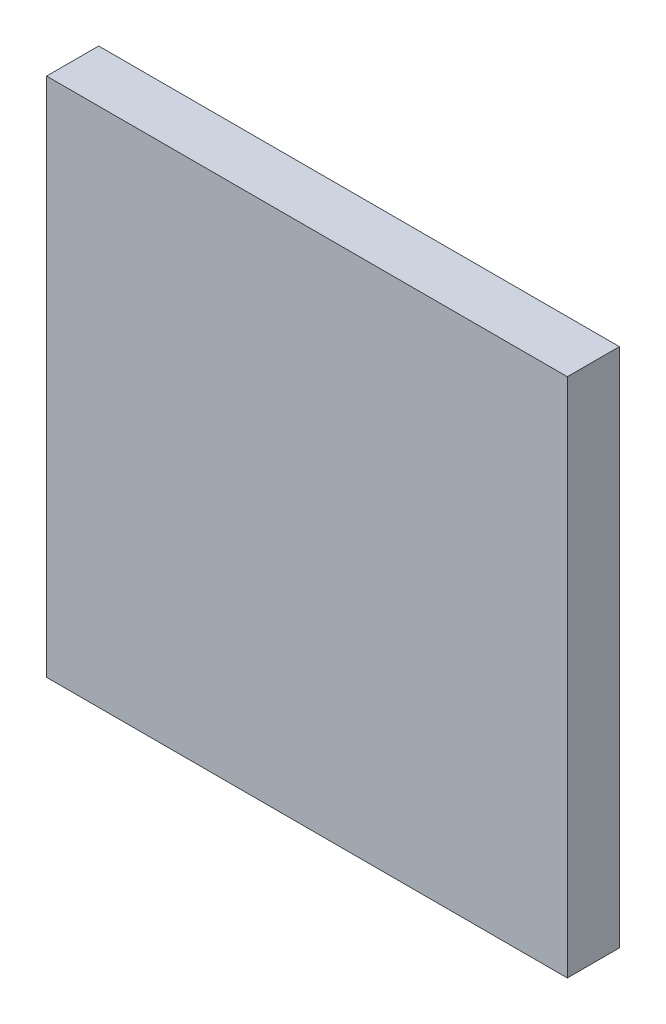
SolidWorks part; units mm, degrees
ref_plane "Plan de face" through (0, 0, 0) normal (0, 0, 1) x (1, 0, 0)
ref_plane "Plan de dessus" through (0, 0, 0) normal (0, 1, 0) x (1, 0, 0)
ref_plane "Plan de droite" through (0, 0, 0) normal (1, 0, 0) x (0, 0, -1)
sketch "Esquisse1" plane through (0, 0, 0) normal (0, 0, 1) x (1, 0, 0)
  line L1 (0, 0) -> (300, 0)
  line L2 (0, 0) -> (0, 300)
  line L3 (0, 300) -> (300, 300)
  line L4 (300, 0) -> (300, 300)
  dimension "D1" = 300
  dimension "D2" = 300
extrude "Boss.-Extru.1" add sketch "Esquisse1" along normal blind 30
